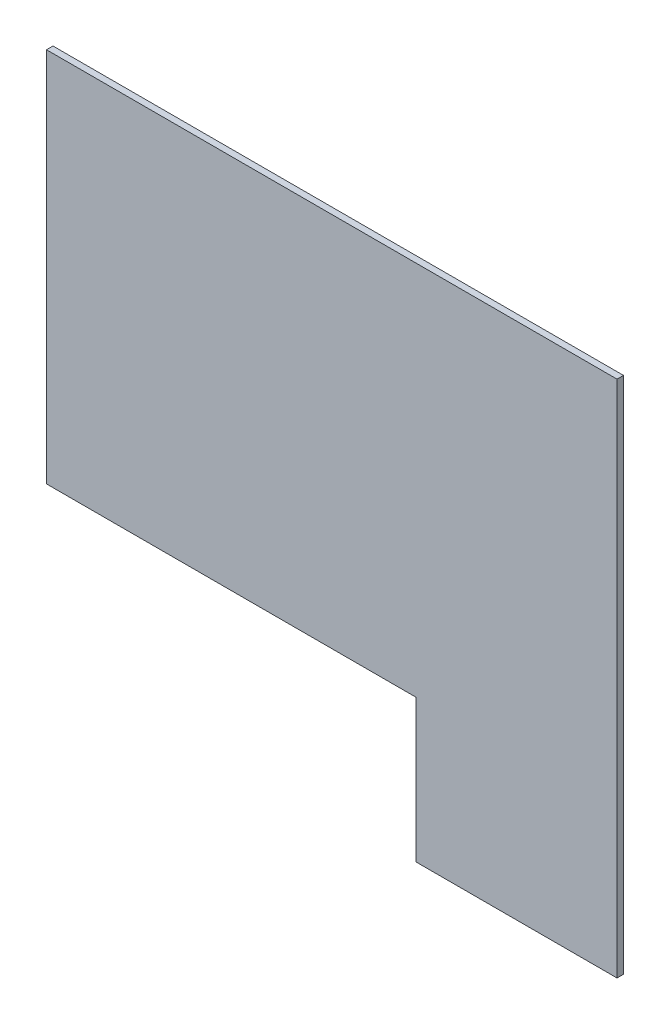
SolidWorks part; units mm, degrees
ref_plane "Alzado" through (0, 0, 0) normal (0, 0, 1) x (1, 0, 0)
ref_plane "Planta" through (0, 0, 0) normal (0, 1, 0) x (1, 0, 0)
ref_plane "Vista lateral" through (0, 0, 0) normal (1, 0, 0) x (0, 0, -1)
sketch "Croquis1" plane through (0, 0, 0) normal (0, 0, 1) x (-1, 0, 0)
  line L19 (-143.5867, 402.2958) -> (-228.5867, 402.2958)
  line L22 (-228.5867, 2.2958) -> (-228.5867, 402.2958)
  line L24 (211.4133, 2.2958) -> (211.4133, 292.2958)
  line L26 (-228.5867, 2.2958) -> (211.4133, 2.2958)
  line L27 (211.4133, 292.2958) -> (-73.5867, 292.2958)
  line L28 (-143.5867, 402.2958) -> (-73.5867, 402.2958)
  line L31 (-73.5867, 402.2958) -> (-73.5867, 292.2958)
  dimension "D1" = 400
  dimension "D2" = 440
  dimension "D3" = 85
  dimension "D4" = 290
  dimension "D5" = 70
extrude "Saliente-Extruir1" add sketch "Croquis1" along normal blind 5
